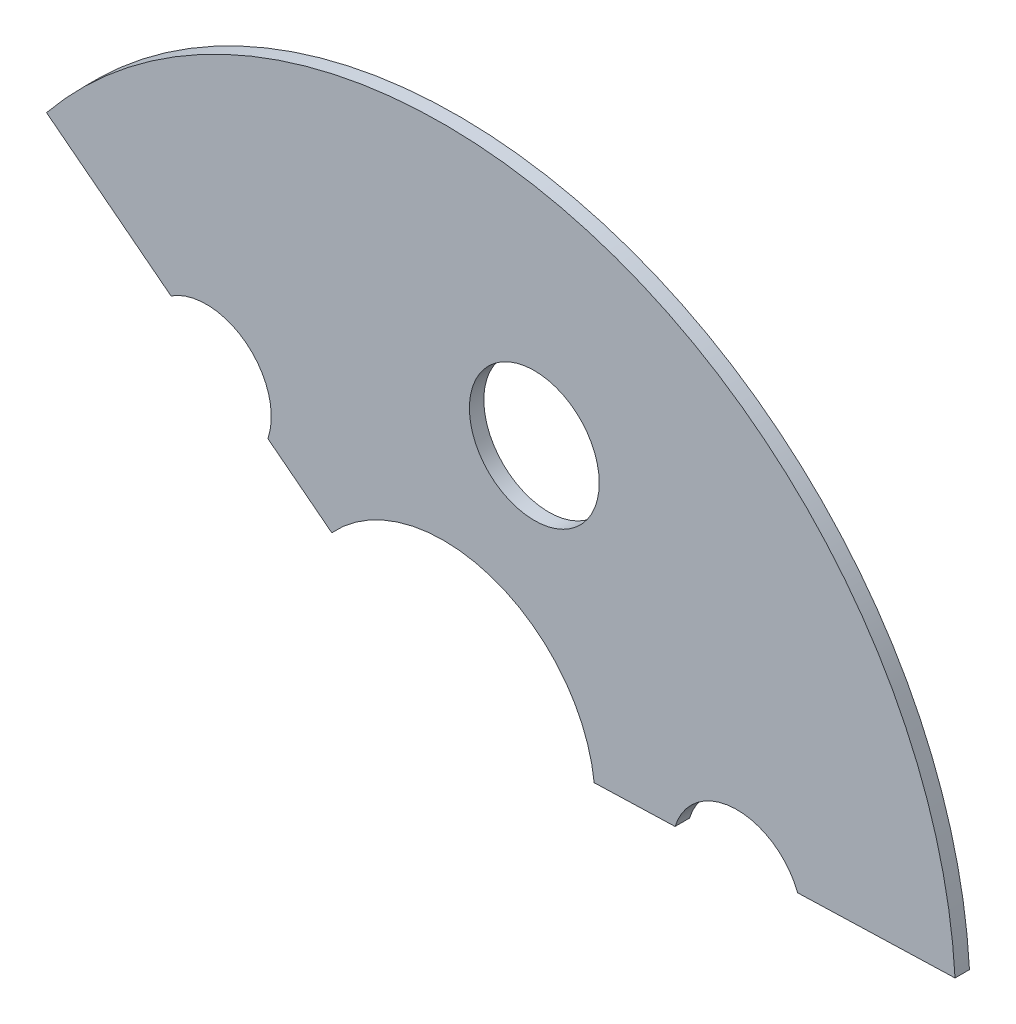
SolidWorks part; units mm, degrees
ref_plane "Front Plane" through (0, 0, 0) normal (0, 0, 1) x (1, 0, 0)
ref_plane "Top Plane" through (0, 0, 0) normal (0, 1, 0) x (1, 0, 0)
ref_plane "Right Plane" through (0, 0, 0) normal (1, 0, 0) x (0, 0, -1)
sketch "Sketch12" plane through (0, 0, 0) normal (0, 0, 1) x (1, 0, 0)
  line L0 (-5.8868, 18.1176) -> (15.4118, 11.1973) construction
  line L1 (0, 38.1) -> (22.3946, 30.8235) construction
  line L2 (11.1973, 34.4618) -> (4.7625, 14.6575) construction
  circle A0 centre (0, 0) radius 50.165
  circle A2 centre (-22.3946, 30.8235) radius 9.5631
  circle A3 centre (0, 38.1) radius 9.5631
  circle A4 centre (22.3946, 30.8235) radius 9.5631
  circle A5 centre (36.2353, 11.7735) radius 9.5631
  circle A6 centre (15.4118, 11.1973) radius 9.6393
  circle A7 centre (-5.8868, 18.1176) radius 9.6393
  circle A8 centre (0, 0) radius 8.255
  circle A9 centre (7.9799, 24.5596) radius 5.715
  point P18 (7.9799, 24.5596)
  dimension "D1" = 19.1262
  dimension "D2" = 16.51
  dimension "D3" = 100.33
  dimension "D4" = 19.2786
  dimension "D15" = 11.43
  dimension "D5" = 15.4118
  dimension "D6" = 22.3946
  dimension "D7" = 36.2353
  dimension "D8" = 5.8868
  dimension "D9" = 22.3946
  dimension "D10" = 11.1973
  dimension "D11" = 11.7735
  dimension "D12" = 18.1176
  dimension "D13" = 30.8235
  dimension "D14" = 38.1
sketch "Sketch13" plane through (0, 0, 0) normal (0, 0, 1) x (1, 0, 0)
  line L1 (-34.961, 28.4672) -> (-9.8479, 8.9912)
  line L2 (22.3946, 30.8235) -> (0, 38.1) construction
  line L3 (0, 0) -> (11.1973, 34.4618) construction
  line L4 (45.0167, 2.4809) -> (13.252, 1.4856)
  arc A0 (13.252, 1.4856) -> (-9.8479, 8.9912) centre (0, 0) ccw
  arc A12 (45.0167, 2.4809) -> (-34.961, 28.4672) centre (0, 0) ccw
  point P15 (11.1973, 34.4618)
  dimension "D1" = 13.335
  dimension "D2" = 45.085
  dimension "D3" = 13.252
  dimension "D4" = 45.0167
extrude "Boss-Extrude1" add sketch "Sketch13" along normal blind 1.27
sketch "Sketch14" plane through (0, 0, 0) normal (0, 0, 1) x (1, 0, 0)
  circle A0 centre (36.2353, 11.7735) radius 1.27 construction
  circle A1 centre (15.4118, 11.1973) radius 1.27 construction
  circle A2 centre (-5.8868, 18.1176) radius 1.27 construction
  circle A3 centre (-22.3946, 30.8235) radius 1.27 construction
  point P0 (36.2353, 11.7735)
  point P1 (15.4118, 11.1973)
  point P3 (-5.8868, 18.1176)
  point P5 (-22.3946, 30.8235)
  point P7 (22.3946, 30.8235)
  point P9 (0, 38.1)
  dimension "D1" = 2.54
  dimension "D2" = 2.54
  dimension "D3" = 2.54
  dimension "D4" = 2.54
sketch "Sketch15" plane through (0, 0, 1.27) normal (0, 0, 1) x (1, 0, 0)
  line L0 (0, 0) -> (-5.8868, 18.1176) construction
  line L1 (0, 0) -> (15.4118, 11.1973) construction
  line L2 (13.252, 1.4856) -> (45.0167, 2.4809) construction
  line L3 (-34.961, 28.4672) -> (-9.8479, 8.9912) construction
  line L4 (13.252, 1.4856) -> (31.1594, 2.0467)
  line L5 (-24.0055, 19.9709) -> (-15.4753, 13.3554)
  circle A0 centre (7.9799, 24.5596) radius 5.715 construction
  circle A1 centre (7.9799, 24.5596) radius 5.715
  arc A2 (-24.0055, 19.9709) -> (-15.4753, 13.3554) centre (-20.8917, 15.1787) cw
  arc A3 (20.3699, 1.7086) -> (31.1594, 2.0467) centre (25.8235, 0) cw
  line M6 (-34.961, 28.4672) -> (-9.8479, 8.9912)
extrude "Cut-Extrude1" cut sketch "Sketch15" against normal through all contours A2 M6 | A1 | A3 L4
